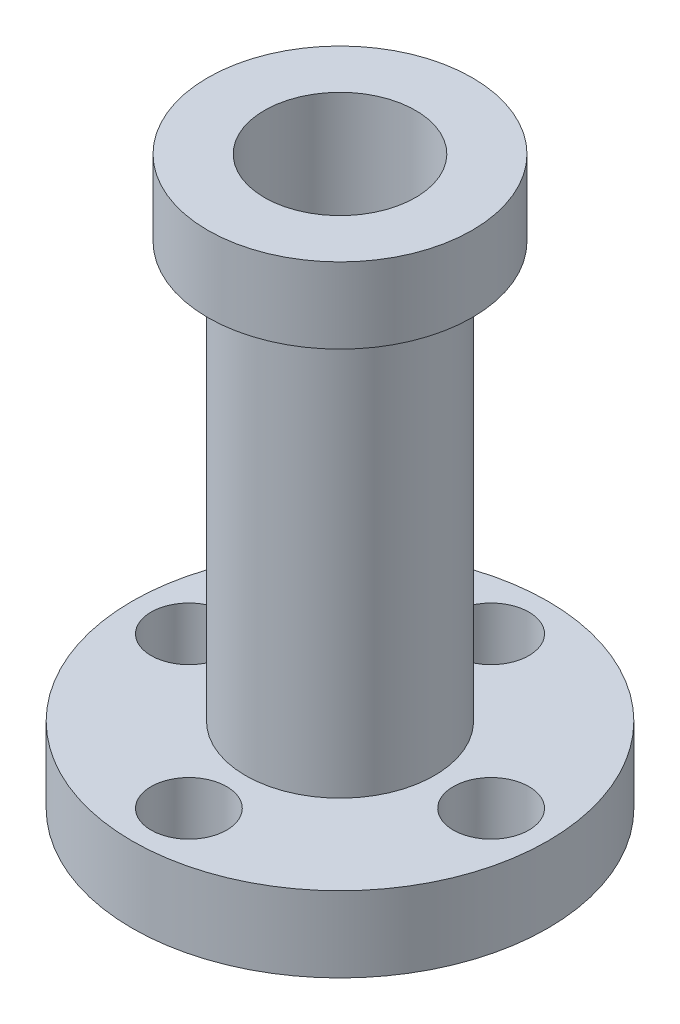
SolidWorks part; units mm, degrees
ref_plane "Спереди" through (0, 0, 0) normal (0, 0, 1) x (1, 0, 0)
ref_plane "Сверху" through (0, 0, 0) normal (0, 1, 0) x (1, 0, 0)
ref_plane "Справа" through (0, 0, 0) normal (1, 0, 0) x (0, 0, -1)
sketch "Эскиз1" plane through (0, 0, 0) normal (0, 0, 1) x (1, 0, 0)
  line L0 (0, 0) -> (0, 30)
  line L1 (0, 30) -> (7, 30)
  line L2 (7, 30) -> (7, 26)
  line L3 (7, 26) -> (5, 26)
  line L4 (5, 26) -> (5, 4)
  line L5 (5, 4) -> (11, 4)
  line L6 (11, 4) -> (11, 0)
  line L7 (11, 0) -> (0, 0)
  dimension "D1" = 4
  dimension "D2" = 5
  dimension "D3" = 11
  dimension "D4" = 4
  dimension "D5" = 7
  dimension "D6" = 30
revolve "Повернуть1" add sketch "Эскиз1" angle 360 about L0
sketch "Эскиз2" plane through (0, 30, 0) normal (0, 1, 0) x (1, 0, 0)
  circle A0 centre (0, 0) radius 4
extrude "Вырез-Вытянуть1" cut sketch "Эскиз2" against normal blind 31.6
sketch "Эскиз4" plane through (0, 4, 0) normal (0, 1, 0) x (1, 0, 0)
  circle A0 centre (0, 0) radius 8 construction
  circle A1 centre (8, 0) radius 2
  circle A2 centre (0, 8) radius 2
  circle A3 centre (-8, 0) radius 2
  circle A4 centre (0, -8) radius 2
  dimension "D1" = 16
  dimension "D2" = 4
extrude "Вырез-Вытянуть2" cut sketch "Эскиз4" against normal blind 31.6
